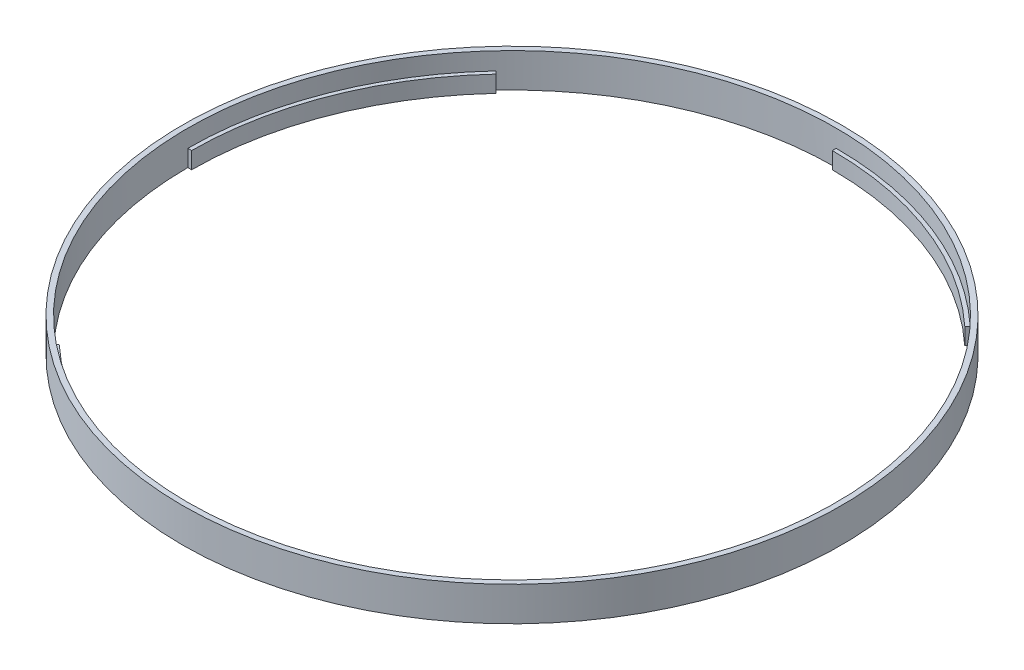
SolidWorks part; units mm, degrees
ref_plane "前视基准面" through (0, 0, 0) normal (0, 0, 1) x (1, 0, 0)
ref_plane "上视基准面" through (0, 0, 0) normal (0, 1, 0) x (1, 0, 0)
ref_plane "右视基准面" through (0, 0, 0) normal (1, 0, 0) x (0, 0, -1)
sketch "草图1" plane through (0, 0, 0) normal (0, 1, 0) x (1, 0, 0)
  circle A0 centre (0, 0) radius 77
  circle A1 centre (0, 0) radius 75.75
  dimension "D1" = 154
  dimension "D2" = 151.5
extrude "凸台-拉伸1" add sketch "草图1" along normal blind 8
sketch "草图2" plane through (0, 0, 0) normal (0, 1, 0) x (1, 0, 0)
  line L0 (0, 0) -> (0, 75.75) construction
  line L1 (0, 0) -> (51.6614, 55.4) construction
  line L2 (0, 75.75) -> (0, 74.85)
  line L3 (51.6614, 55.4) -> (51.0476, 54.7418)
  line L4 (55.4, -51.6614) -> (54.7418, -51.0476)
  line L5 (75.75, 0) -> (74.85, 0)
  line L6 (-51.6614, -55.4) -> (-51.0476, -54.7418)
  line L7 (0, -75.75) -> (0, -74.85)
  line L8 (-55.4, 51.6614) -> (-54.7418, 51.0476)
  line L9 (-75.75, 0) -> (-74.85, 0)
  arc A0 (51.0476, 54.7418) -> (0, 74.85) centre (0, 0) ccw
  circle A1 centre (0, 0) radius 75.75 construction
  arc A2 (51.6614, 55.4) -> (0, 75.75) centre (0, 0) ccw
  arc A3 (54.7418, -51.0476) -> (74.85, 0) centre (0, 0) ccw
  arc A4 (55.4, -51.6614) -> (75.75, 0) centre (0, 0) ccw
  arc A5 (-51.0476, -54.7418) -> (0, -74.85) centre (0, 0) ccw
  arc A6 (-51.6614, -55.4) -> (0, -75.75) centre (0, 0) ccw
  arc A7 (-54.7418, 51.0476) -> (-74.85, 0) centre (0, 0) ccw
  arc A8 (-55.4, 51.6614) -> (-75.75, 0) centre (0, 0) ccw
  point P24 (0, 0)
  dimension "D2" = 149.7
  dimension "D1" = 43
  dimension "D3" = 4
extrude "凸台-拉伸2" add sketch "草图2" along normal blind 3.9
sketch "草图3" plane through (0, 0, 0) normal (0, -1, 0) x (1, 0, 0)
  circle A0 centre (0, 0) radius 78
  circle A1 centre (0, 0) radius 75.75
extrude "凸台-拉伸3" [suppressed] add sketch "草图3" along normal blind 2
